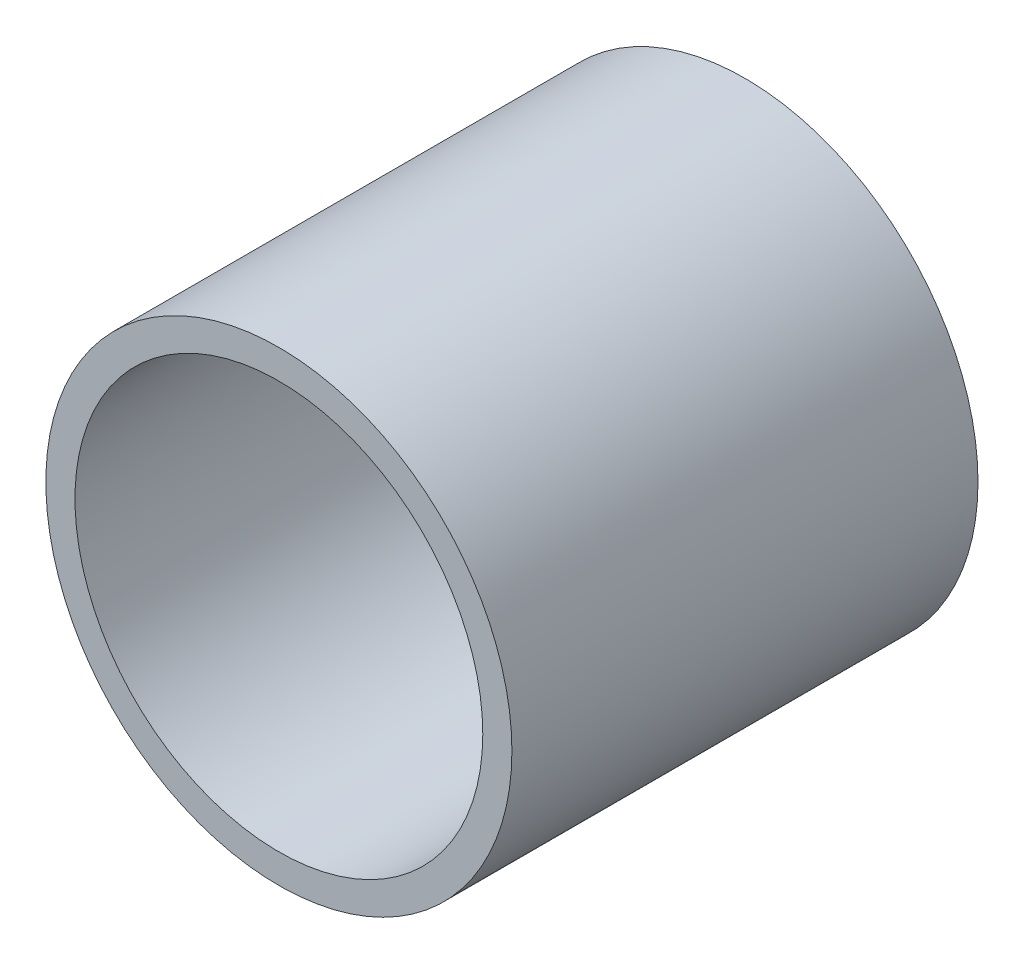
SolidWorks part; units mm, degrees
ref_plane "前视基准面" through (0, 0, 0) normal (0, 0, 1) x (1, 0, 0)
ref_plane "上视基准面" through (0, 0, 0) normal (0, 1, 0) x (1, 0, 0)
ref_plane "右视基准面" through (0, 0, 0) normal (1, 0, 0) x (0, 0, -1)
sketch "Sketch1" plane through (0, 0, 0) normal (0, 0, 1) x (1, 0, 0)
  circle A0 centre (0, 0) radius 4
  circle A1 centre (0, 0) radius 3.5
  dimension "D1" = 8
  dimension "D2" = 7
extrude "Boss-Extrude1" add sketch "Sketch1" along normal blind 8
